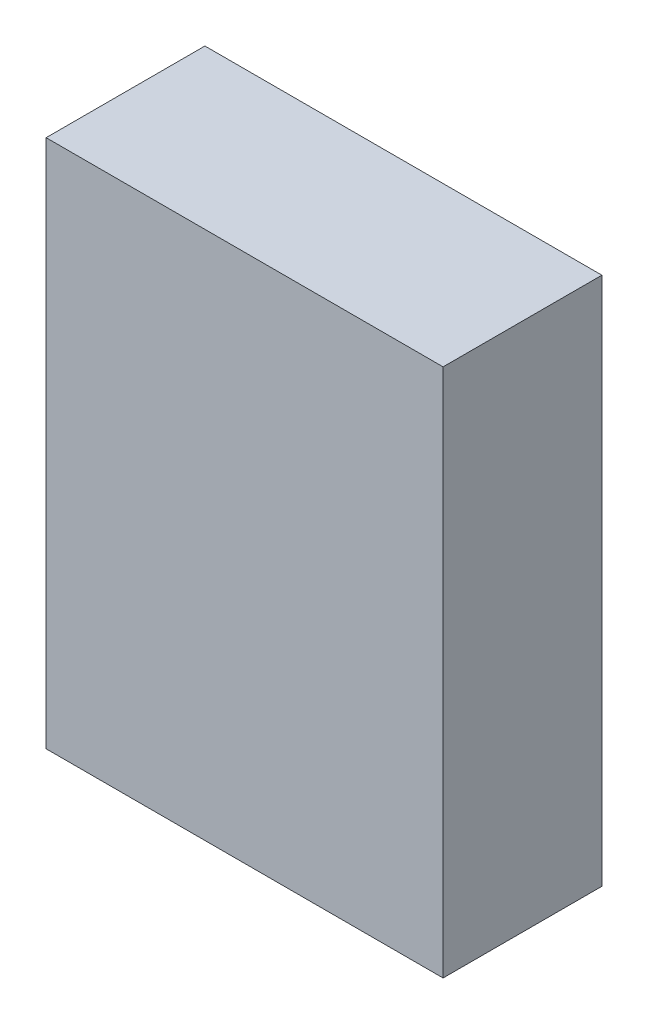
SolidWorks part; units mm, degrees
ref_plane "Front Plane" through (0, 0, 0) normal (0, 0, 1) x (1, 0, 0)
ref_plane "Top Plane" through (0, 0, 0) normal (0, 1, 0) x (1, 0, 0)
ref_plane "Right Plane" through (0, 0, 0) normal (1, 0, 0) x (0, 0, -1)
sketch "Sketch1" plane through (0, 0, 0) normal (0, 0, 1) x (1, 0, 0)
  line L1 (-37.5, 50) -> (37.5, 50)
  line L2 (-37.5, 50) -> (-37.5, -50)
  line L3 (-37.5, -50) -> (37.5, -50)
  line L4 (37.5, 50) -> (37.5, -50)
  line L5 (-37.5, 50) -> (37.5, -50) construction
  line L6 (-37.5, -50) -> (37.5, 50) construction
  point P0 (0, 0)
  dimension "D1" = 100
  dimension "D2" = 75
extrude "Boss-Extrude1" add sketch "Sketch1" along normal blind 30
